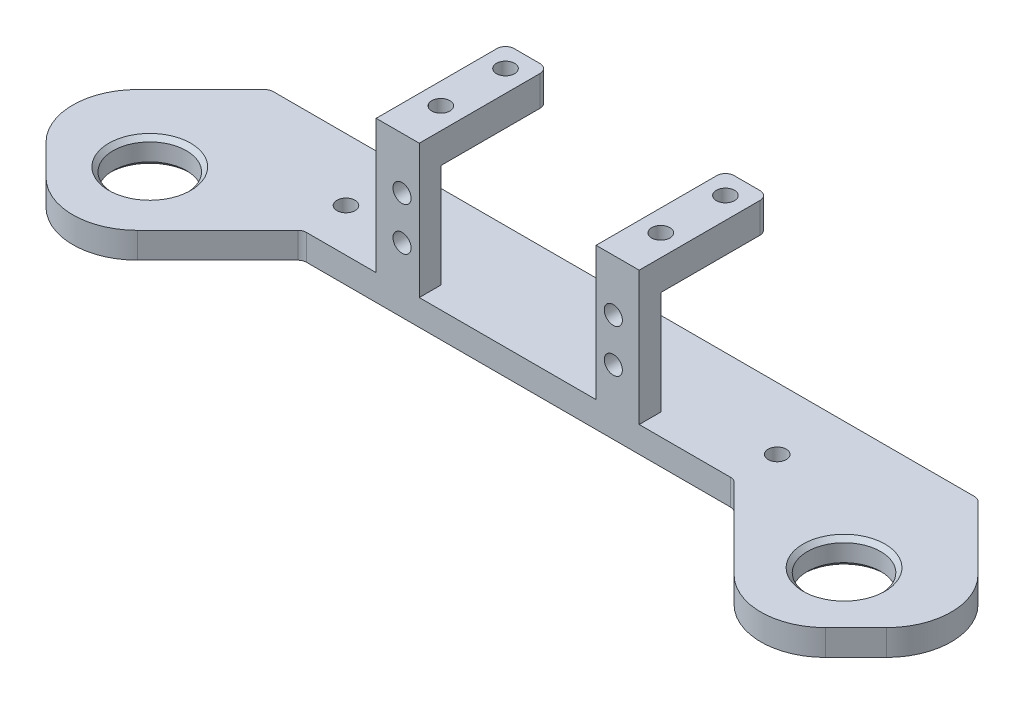
SolidWorks part; units mm, degrees
ref_plane "前视基准面" through (0, 0, 0) normal (0, 0, 1) x (1, 0, 0)
ref_plane "上视基准面" through (0, 0, 0) normal (0, 1, 0) x (1, 0, 0)
ref_plane "右视基准面" through (0, 0, 0) normal (1, 0, 0) x (0, 0, -1)
sketch "草图1" plane through (0, 0, 0) normal (0, 1, 0) x (1, 0, 0)
  line L0 (0, 0) -> (100, 0)
  line L1 (100, 0) -> (129.7817, -29.7817)
  line L2 (129.7817, -29.7817) -> (158.066, -1.4975)
  line L3 (158.066, -1.4975) -> (132.1371, 24.4315)
  line L6 (70, 24.4315) -> (30, 24.4315)
  line L9 (-32.1371, 24.4315) -> (-58.066, -1.4975)
  line L10 (-58.066, -1.4975) -> (-29.7817, -29.7817)
  line L11 (-29.7817, -29.7817) -> (0, 0)
  line L12 (50, 0) -> (50, 24.4315) construction
  line L13 (0, 0) -> (142.3785, 0) construction
  line L14 (30, 24.4315) -> (-32.1371, 24.4315)
  line L15 (70, 24.4315) -> (132.1371, 24.4315)
  circle A0 centre (-30.5, -5) radius 8.5
  circle A1 centre (130.5, -5) radius 8.5
  circle A4 centre (0, 10) radius 2.1
  circle A5 centre (100, 10) radius 2.1
  point P14 (50, 24.4315)
  point P17 (50, 0)
  dimension "D6" = 80.5
  dimension "D9" = 15
  dimension "D2" = 15
  dimension "D3" = 135
  dimension "D4" = 135
  dimension "D5" = 100
  dimension "D7" = 80.5
  dimension "D8" = 40
  dimension "D10" = 40
  dimension "D11" = 5
  dimension "D12" = 5
  dimension "D13" = 100
  dimension "D14" = 50
  dimension "D15" = 40
extrude "凸台-拉伸1" add sketch "草图1" along normal blind 6
fillet "圆角1" radius 15 4 edges at (129.7817, 3, 29.7817) (-29.7817, 3, 29.7817) (158.066, 3, 1.4975) (-58.066, 3, 1.4975)
fillet "圆角2" radius 2 2 edges at (100, 3, 0) (0, 3, 0)
sketch "草图2" plane through (0, 0, 0) normal (0, 0, 1) x (1, 0, 0)
  line L0 (50, 0) -> (50, 11.9154) construction
  line L1 (0.8284, 6) -> (99.1716, 6) construction
  line L2 (23, 6) -> (27, 6)
  line L3 (27, 6) -> (27, 30)
  line L4 (27, 30) -> (17, 30)
  line L5 (17, 30) -> (17, 6)
  line L6 (17, 6) -> (23, 6)
  line L7 (72, 6) -> (68, 6)
  line L8 (68, 6) -> (68, 30)
  line L9 (68, 30) -> (78, 30)
  line L10 (78, 30) -> (78, 6)
  line L11 (78, 6) -> (72, 6)
  line L12 (23, 6) -> (23, 22.9952) construction
  line L13 (72, 6) -> (72, 16.7294) construction
  line L14 (17, 6) -> (17, 0)
  line L15 (0.8284, 0) -> (99.1716, 0) construction
  line L16 (17, 0) -> (27, 0)
  line L17 (27, 0) -> (27, 6)
  line L18 (68, 6) -> (68, 0)
  line L19 (68, 0) -> (78, 0)
  line L20 (78, 0) -> (78, 6)
  circle A0 centre (23, 15) radius 2.1
  circle A1 centre (23, 25) radius 2.1
  circle A2 centre (72, 25) radius 2.1
  circle A3 centre (72, 15) radius 2.1
  point P1 (23, 6)
  point P2 (72, 6)
  line M15 (0.8284, 0) -> (99.1716, 0)
  line M17 (99.1716, 6) -> (0.8284, 6)
  dimension "D9" = 4.2
  dimension "D10" = 4.2
  dimension "D11" = 4.2
  dimension "D12" = 4.2
  dimension "D1" = 27
  dimension "D2" = 22
  dimension "D3" = 4
  dimension "D4" = 4
  dimension "D5" = 24
  dimension "D6" = 24
  dimension "D7" = 10
  dimension "D8" = 10
  dimension "D13" = 10
  dimension "D14" = 10
  dimension "D15" = 9
  dimension "D16" = 9
extrude "凸台-拉伸2" add sketch "草图2" against normal blind 5 contours L4 L5 L3 A1 A0 M17 | L17 L14 M15 M17 | L10 L9 L8 A3 A2 M17 | L20 L18 M15 M17
sketch "草图3" plane through (0, 30, 0) normal (0, 1, 0) x (1, 0, 0)
  line L0 (17, 0) -> (17, 30)
  line L1 (17, 30) -> (27, 30)
  line L2 (27, 30) -> (27, 0)
  line L3 (68, 0) -> (68, 30)
  line L4 (68, 30) -> (78, 30)
  line L5 (78, 30) -> (78, 0)
  line L6 (22, 0) -> (22, 33.9217) construction
  line L7 (50, 24.4315) -> (50, 48.0655) construction
  line L8 (73, 0) -> (73, 36.7107) construction
  line L10 (27, 0) -> (17, 0) construction
  line L11 (68, 0) -> (78, 0) construction
  line L12 (68, 0) -> (78, 0)
  line L13 (27, 0) -> (17, 0)
  circle A0 centre (22, 25) radius 2.1
  circle A1 centre (73, 25) radius 2.1
  circle A2 centre (73, 10) radius 2.1
  circle A3 centre (22, 10) radius 2.1
  point P28 (22, 0)
  point P29 (73, 0)
  point P30 (22, 0)
  dimension "D3" = 4.2
  dimension "D4" = 4.2
  dimension "D5" = 4.2
  dimension "D6" = 4.2
  dimension "D1" = 30
  dimension "D2" = 30
  dimension "D7" = 15
  dimension "D8" = 15
  dimension "D9" = 10
  dimension "D10" = 10
extrude "凸台-拉伸3" add sketch "草图3" along normal blind 7
fillet "圆角4" radius 2 4 edges at (17, 33.5, -30) (68, 33.5, -30) (78, 33.5, -30) (27, 33.5, -30)
fillet "圆角5" radius 2 2 edges at (-32.1371, 3, -24.4315) (132.1371, 3, -24.4315)
chamfer "倒角1" distance 1 angle 45 4 edges at (-30.5, 0, 13.5) (-30.5, 6, 13.5) (130.5, 6, 13.5) (130.5, 0, 13.5)
